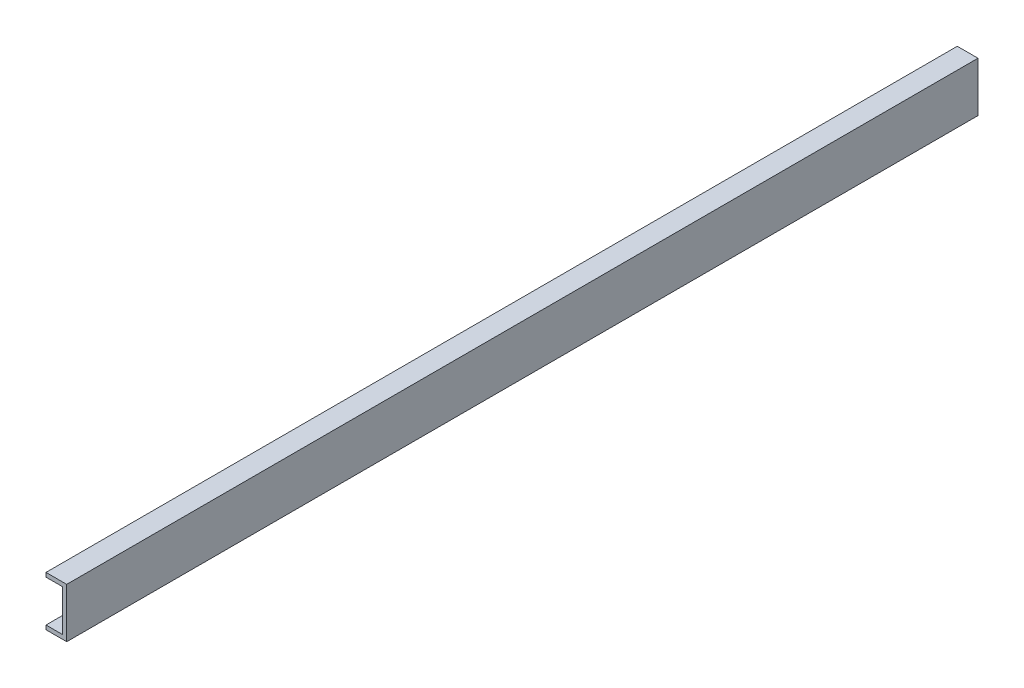
SolidWorks part; units mm, degrees
material "Galvanized Steel"
ref_plane "Front Plane" through (0, 0, 0) normal (0, 0, 1) x (1, 0, 0)
ref_plane "Top Plane" through (0, 0, 0) normal (0, 1, 0) x (1, 0, 0)
ref_plane "Right Plane" through (0, 0, 0) normal (1, 0, 0) x (0, 0, -1)
sketch "Sketch1" plane through (0, 0, 0) normal (0, 0, 1) x (1, 0, 0)
  line L1 (-6.35, -15.24) -> (6.35, -15.24)
  line L2 (-6.35, -15.24) -> (-6.35, 15.24)
  line L3 (-6.35, 15.24) -> (6.35, 15.24)
  line L4 (6.35, -15.24) -> (6.35, 15.24)
  line L5 (-6.35, -15.24) -> (6.35, 15.24) construction
  line L6 (-6.35, 15.24) -> (6.35, -15.24) construction
  point P0 (0, 0)
  dimension "D1" = 30.48
  dimension "D2" = 12.7
extrude "Boss-Extrude1" add sketch "Sketch1" along normal blind 558.8
sketch "Sketch2" plane through (0, 0, 558.8) normal (0, 0, 1) x (1, 0, 0)
  line L0 (-6.35, 15.24) -> (-6.35, -15.24) construction
  line L1 (-6.35, 12.7) -> (3.81, 12.7)
  line L2 (-6.35, 12.7) -> (-6.35, -12.7)
  line L3 (-6.35, -12.7) -> (3.81, -12.7)
  line L4 (3.81, 12.7) -> (3.81, -12.7)
  line L5 (6.35, 15.24) -> (-6.35, 15.24) construction
  line L6 (6.35, -15.24) -> (6.35, 15.24) construction
  line L7 (-6.35, -15.24) -> (6.35, -15.24) construction
  dimension "D1" = 2.54
  dimension "D2" = 2.54
  dimension "D3" = 2.54
extrude "Cut-Extrude1" cut sketch "Sketch2" against normal through all
